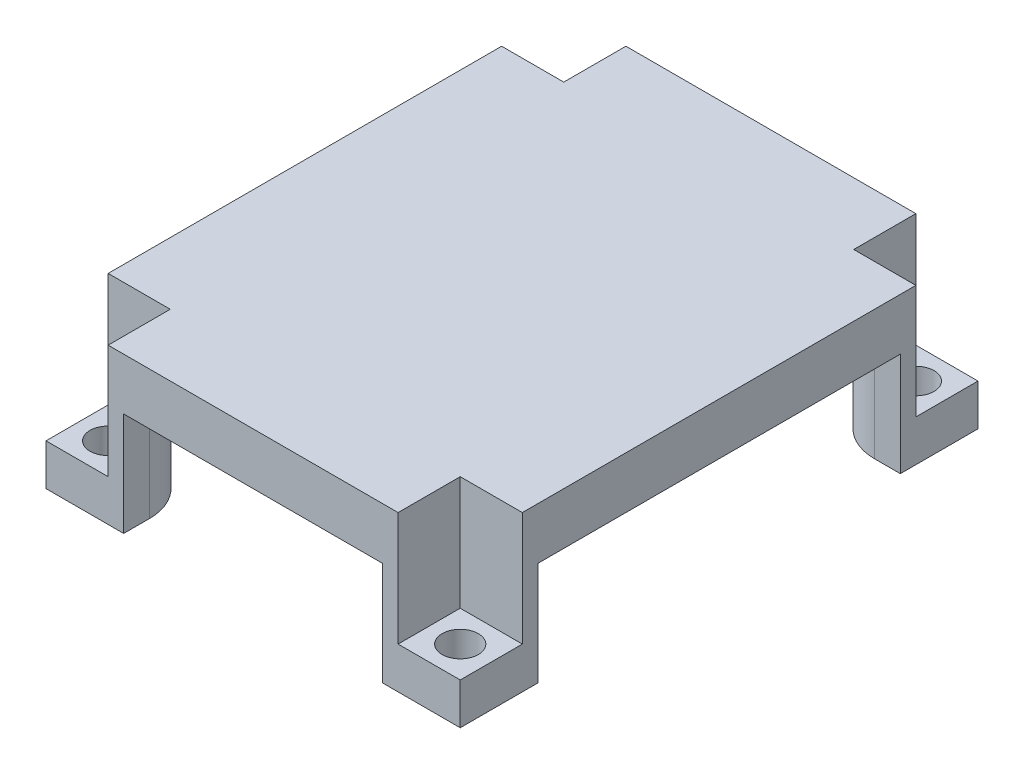
SolidWorks part; units mm, degrees
ref_plane "Alzado" through (0, 0, 0) normal (0, 0, 1) x (1, 0, 0)
ref_plane "Planta" through (0, 0, 0) normal (0, 1, 0) x (1, 0, 0)
ref_plane "Vista lateral" through (0, 0, 0) normal (1, 0, 0) x (0, 0, -1)
sketch "Croquis1" plane through (0, 0, 0) normal (0, 1, 0) x (1, 0, 0)
  line L1 (-20, -25) -> (20, -25)
  line L2 (-20, -25) -> (-20, 25)
  line L3 (-20, 25) -> (20, 25)
  line L4 (20, -25) -> (20, 25)
  line L5 (-20, -25) -> (20, 25) construction
  line L6 (-20, 25) -> (20, -25) construction
  point P0 (0, 0)
  dimension "D1" = 40
  dimension "D2" = 50
extrude "Saliente-Extruir1" add sketch "Croquis1" along normal blind 15
sketch "Croquis2" plane through (0, 15, 0) normal (0, 1, 0) x (1, 0, 0)
  line L0 (-20, 25) -> (-20, -25) construction
  line L1 (20, 25) -> (-20, 25) construction
  circle A0 centre (-17, 22) radius 1.75
  dimension "D1" = 3.5
  dimension "D2" = 3
  dimension "D3" = 3
extrude "Cortar-Extruir1" cut sketch "Croquis2" against normal blind 15 contours A0
mirror "Simetría1" about plane through (0, 0, 0) normal (1, 0, 0) of "Cortar-Extruir1"
mirror "Simetría2" about plane through (0, 0, 0) normal (0, 0, 1) of "Simetría1", "Cortar-Extruir1"
sketch "Croquis3" plane through (0, 15, 0) normal (0, 1, 0) x (1, 0, 0)
  line L1 (-14, 19) -> (-20, 19)
  line L2 (-14, 19) -> (-14, 25)
  line L3 (-14, 25) -> (-20, 25)
  line L4 (-20, 19) -> (-20, 25)
  line L5 (-14, 19) -> (-20, 25) construction
  line L6 (-14, 25) -> (-20, 19) construction
  point P0 (-17, 22)
extrude "Cortar-Extruir6" cut sketch "Croquis3" against normal blind 11
mirror "Simetría3" about plane through (0, 0, 0) normal (1, 0, 0) of "Cortar-Extruir6"
mirror "Simetría4" about plane through (0, 0, 0) normal (0, 0, 1) of "Simetría3", "Cortar-Extruir6"
sketch "Croquis4" plane through (-20, 0, 0) normal (-1, 0, 0) x (0, 0, 1)
  line L0 (22, 0) -> (-22, 0) construction
  line L1 (-17.5, 0) -> (17.5, 0)
  line L2 (-17.5, 0) -> (-17.5, 10)
  line L3 (-17.5, 10) -> (17.5, 10)
  line L4 (17.5, 0) -> (17.5, 10)
  line L6 (0, -8.25) -> (0, 8.25) construction
  dimension "D1" = 10
  dimension "D2" = 35
  dimension "D3" = 17.5
extrude "Cortar-Extruir7" cut sketch "Croquis4" against normal through all
sketch "Croquis5" plane through (0, 0, 25) normal (0, 0, 1) x (1, 0, 0)
  line L0 (22, 0) -> (-22, 0) construction
  line L1 (-12.5, 0) -> (12.5, 0)
  line L2 (-12.5, 0) -> (-12.5, 10)
  line L3 (-12.5, 10) -> (12.5, 10)
  line L4 (12.5, 0) -> (12.5, 10)
  line L5 (0, -8.25) -> (0, 8.25) construction
  dimension "D1" = 25
  dimension "D2" = 10
  dimension "D3" = 12.5
extrude "Cortar-Extruir8" cut sketch "Croquis5" against normal through all
fillet "Redondeo1" radius 5 4 edges at (12.5, 5, -17.5) (12.5, 5, 17.5) (-12.5, 5, 17.5) (-12.5, 5, -17.5)
